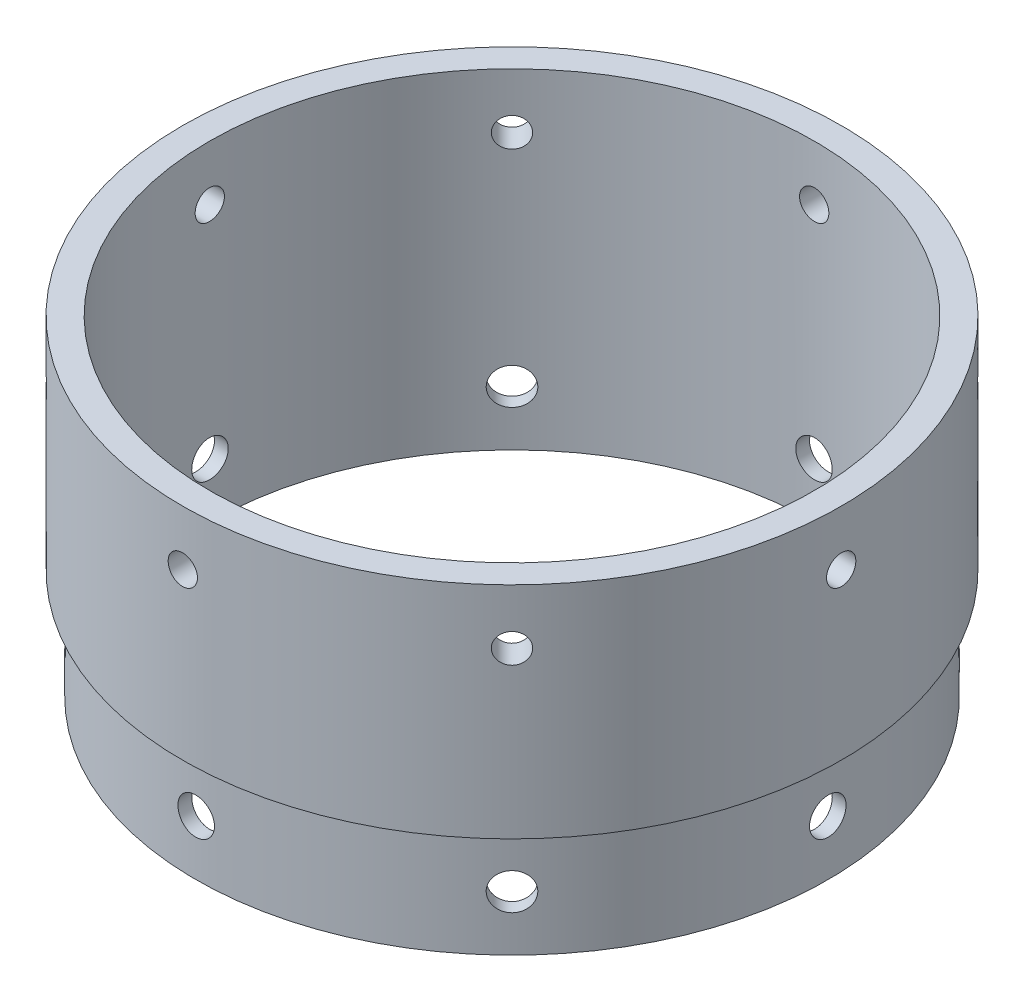
SolidWorks part; units mm, degrees
material "6061-T6 (SS)"
ref_plane "Front Plane" through (0, 0, 0) normal (0, 0, 1) x (1, 0, 0)
ref_plane "Top Plane" through (0, 0, 0) normal (0, 1, 0) x (1, 0, 0)
ref_plane "Right Plane" through (0, 0, 0) normal (1, 0, 0) x (0, 0, -1)
sketch "Sketch1" plane through (0, 0, 0) normal (0, 0, 1) x (1, 0, 0)
  line L0 (0, 77.8484) -> (0, -41.4736) construction
  line L1 (73.025, 0) -> (73.025, 25.4)
  line L2 (73.025, 25.4) -> (76.073, 25.4)
  line L3 (76.073, 25.4) -> (76.073, 76.2)
  line L4 (76.073, 76.2) -> (69.85, 76.2)
  line L5 (69.85, 76.2) -> (69.85, 0)
  line L6 (69.85, 0) -> (73.025, 0)
  dimension "D1" = 25.4
  dimension "D2" = 50.8
  dimension "D3" = 152.146
  dimension "D4" = 146.05
  dimension "D5" = 139.7
revolve "Revolve1" add sketch "Sketch1" angle 360 about L0
ref_plane "Plane1" through (0, 0, 76.073) normal (0, 0, 1) x (1, 0, 0)
hole_wizard "5/16 Clearance Hole1" positions "Sketch2" profile "Sketch4" hole size "5/16" standard "ANSI Inch"
sketch "Sketch2" plane through (0, 0, 76.073) normal (0, 0, 1) x (1, 0, 0)
  line L0 (-73.025, 0) -> (73.025, 0) construction
  point P0 (0, 12.7)
  dimension "D1" = 12.7
sketch "Sketch4" plane through (0, 12.7, 76.073) normal (1, 0, 0) x (0, -1, 0)
  line L0 (0, 0) -> (0, 19.304)
  line L1 (0, 19.304) -> (4.2164, 16.7705)
  line L2 (4.2164, 16.7705) -> (4.2164, 0)
  line L5 (4.2164, 0) -> (0, 0)
  line L10 (0, 19.304) -> (-4.2164, 16.7705) construction
  line L11 (0, -6.35) -> (0, 107.95) construction
  dimension "Hole Dia." = 8.4328
  dimension "Hole Depth" = 19.304
  dimension "Drill Angle" = 118
hole_wizard "1/4 Clearance Hole1" positions "Sketch6" profile "Sketch5" hole size "1/4" standard "ANSI Inch"
sketch "Sketch6" plane through (0, 0, 76.073) normal (0, 0, 1) x (1, 0, 0)
  line L0 (76.073, 76.2) -> (-76.073, 76.2) construction
  point P0 (0, 63.5)
  dimension "D1" = 12.7
sketch "Sketch5" plane through (0, 63.5, 76.073) normal (1, 0, 0) x (0, -1, 0)
  line L0 (0, 0) -> (0, 16.51)
  line L1 (0, 16.51) -> (3.3782, 14.4802)
  line L2 (3.3782, 14.4802) -> (3.3782, 0)
  line L5 (3.3782, 0) -> (0, 0)
  line L10 (0, 16.51) -> (-3.3782, 14.4802) construction
  line L11 (0, -6.35) -> (0, 107.95) construction
  dimension "Hole Dia." = 6.7564
  dimension "Hole Depth" = 16.51
  dimension "Drill Angle" = 118
pattern_circular "CirPattern1" count 8 over 360 about axis through (0, 77.8484, 0) along (0, 1, 0) of "1/4 Clearance Hole1", "5/16 Clearance Hole1"
